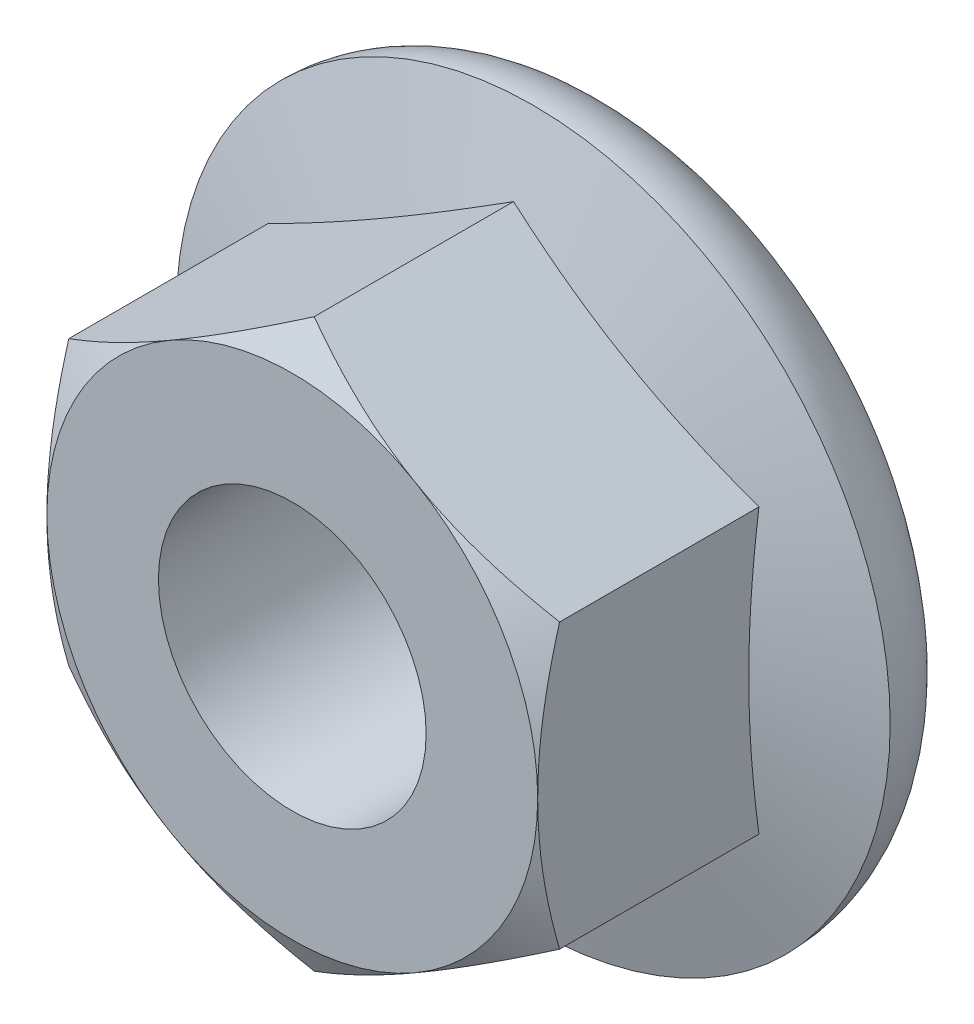
SolidWorks part; units mm, degrees
ref_plane "Front" through (0, 0, 0) normal (0, 0, 1) x (1, 0, 0)
ref_plane "Top" through (0, 0, 0) normal (0, 1, 0) x (1, 0, 0)
ref_plane "Right" through (0, 0, 0) normal (1, 0, 0) x (0, 0, -1)
ref_plane "Plane1" through (0, 0, 1) normal (0, 0, 1) x (1, 0, 0)
sketch "Sketch1" plane through (0, 0, 1) normal (0, 0, 1) x (1, 0, 0)
  line L1 (0, 3.1754) -> (-2.75, 1.5877)
  line L2 (-2.75, 1.5877) -> (-2.75, -1.5877)
  line L3 (-2.75, -1.5877) -> (0, -3.1754)
  line L4 (0, -3.1754) -> (2.75, -1.5877)
  line L5 (2.75, -1.5877) -> (2.75, 1.5877)
  line L6 (2.75, 1.5877) -> (0, 3.1754)
  circle A0 centre (0, 0) radius 2.75 construction
  dimension "S" = 5.5
extrude "Extrude1" add sketch "Sketch1" along normal blind 2.7
sketch "Sketch2" plane through (0, 0, 0) normal (1, 0, 0) x (0, 0, -1)
  line L0 (0, 0) -> (0, 3)
  line L1 (-1, 4) -> (-2.0718, 0)
  line L2 (-2.0718, 0) -> (0, 0)
  line L3 (0, 0) -> (-3.7, 0) construction
  line L4 (-3.7, -1.5877) -> (-3.7, 1.5877) construction
  arc A0 (0, 3) -> (-1, 4) centre (-1, 3) ccw
  dimension "A" = 15
  dimension "c" = 1
  dimension "dc" = 8
revolve "Revolve1" add sketch "Sketch2" angle 360 about L3
sketch "Sketch3" plane through (0, 0, 0) normal (0, 1, 0) x (1, 0, 0)
  line L0 (-2.75, -3.7) -> (-3.85, -3.7)
  line L1 (-3.85, -3.7) -> (-3.85, -3.0649)
  line L2 (-3.85, -3.0649) -> (-2.75, -3.7)
  line L3 (0, 0) -> (0, -3.7) construction
  dimension "D1" = 30
  dimension "D2" = 1.1
revolve "Cut-Revolve1" cut sketch "Sketch3" angle 360 about L3
sketch "Sketch4" plane through (0, 0, 0) normal (0, 0, -1) x (-1, 0, 0)
  circle A0 centre (0, 0) radius 1.5
  dimension "d" = 3
extrude "Cut-Extrude1" cut sketch "Sketch4" against normal through all
equation "\"D2@Sketch3\" = \"S@Sketch1\" / 5"
